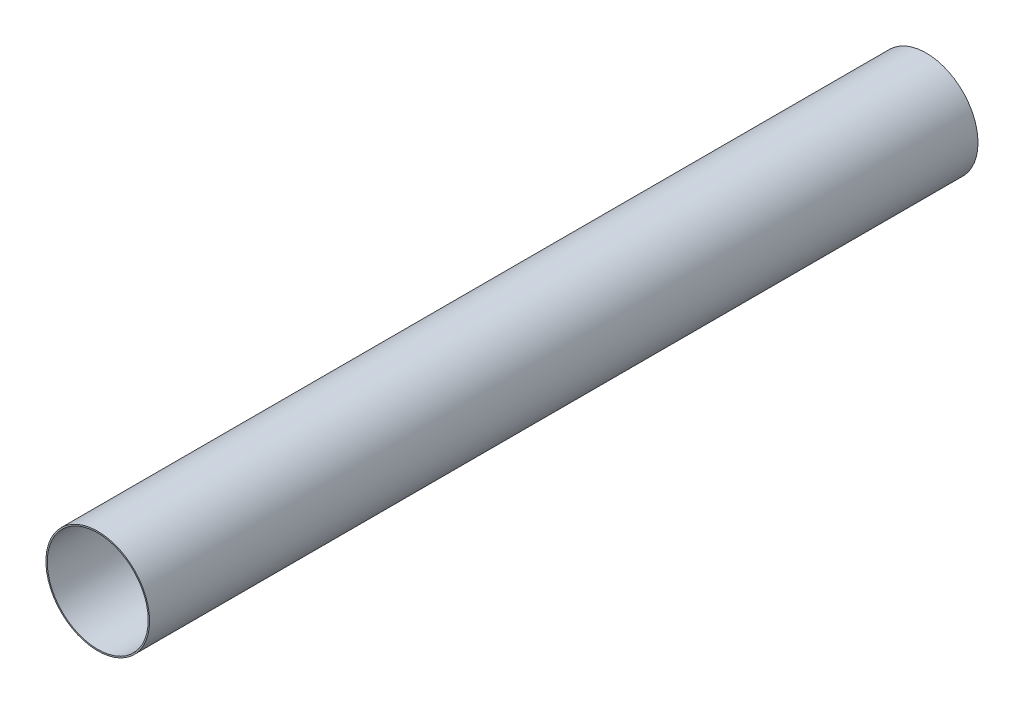
SolidWorks part; units mm, degrees
material "E-Glass Fiber"
ref_plane "Front" through (0, 0, 0) normal (0, 0, 1) x (1, 0, 0)
ref_plane "Top" through (0, 0, 0) normal (0, 1, 0) x (1, 0, 0)
ref_plane "Right" through (0, 0, 0) normal (1, 0, 0) x (0, 0, -1)
sketch "Sketch1" plane through (0, 0, 0) normal (0, 0, 1) x (1, 0, 0)
  circle A0 centre (0, 0) radius 78.2
  circle A1 centre (0, 0) radius 76.2
  dimension "D1" = 156.4
  dimension "D2" = 152.4
extrude "Boss-Extrude1" add sketch "Sketch1" along normal blind 1250
